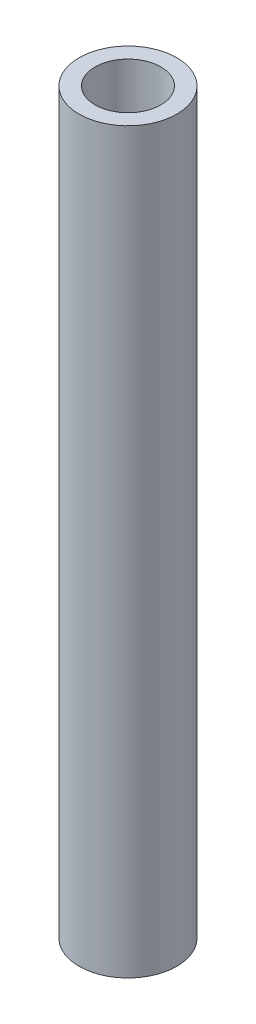
SolidWorks part; units mm, degrees
ref_plane "Спереди" through (0, 0, 0) normal (0, 0, 1) x (1, 0, 0)
ref_plane "Сверху" through (0, 0, 0) normal (0, 1, 0) x (1, 0, 0)
ref_plane "Справа" through (0, 0, 0) normal (1, 0, 0) x (0, 0, -1)
sketch "Эскиз1" plane through (0, 0, 0) normal (0, 1, 0) x (1, 0, 0)
  circle A0 centre (0, 0) radius 2.45
  circle A1 centre (0, 0) radius 1.65
  dimension "D1" = 3.3
  dimension "D2" = 4.9
extrude "Бобышка-Вытянуть1" add sketch "Эскиз1" along normal mid plane 37
